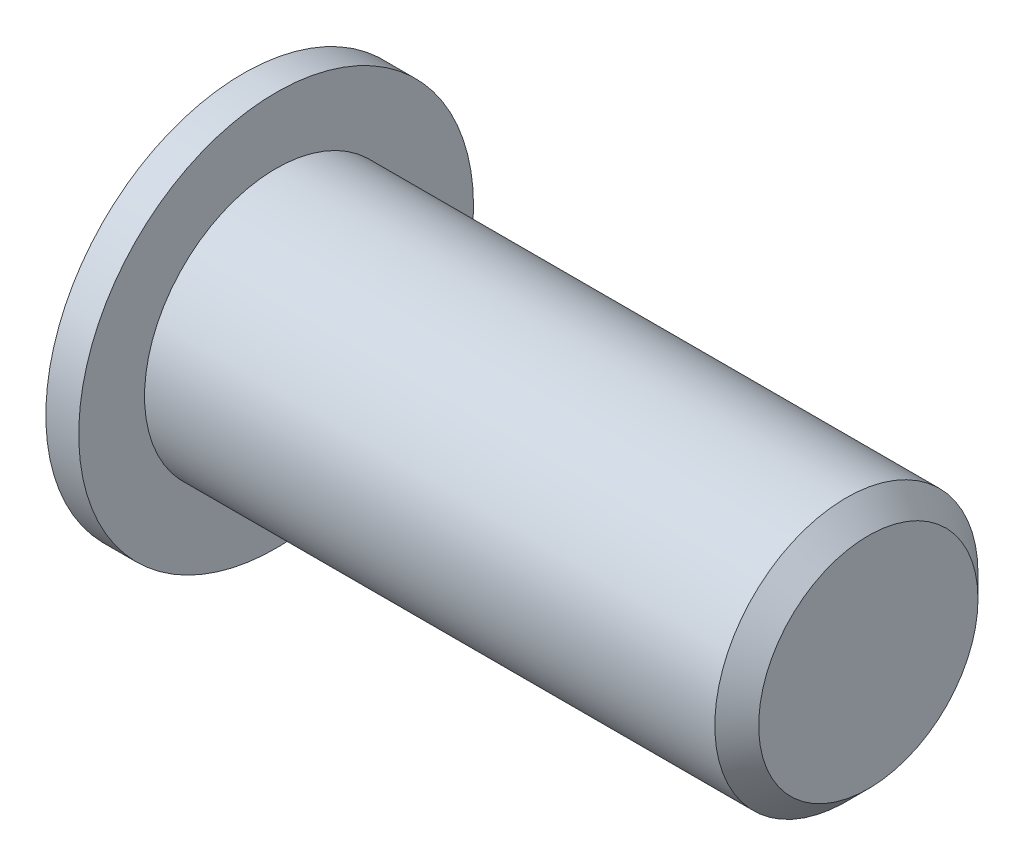
SolidWorks part; units mm, degrees
ref_plane "Front Plane" through (0, 0, 0) normal (0, 0, 1) x (1, 0, 0)
ref_plane "Top Plane" through (0, 0, 0) normal (0, 1, 0) x (1, 0, 0)
ref_plane "Right Plane" through (0, 0, 0) normal (1, 0, 0) x (0, 0, -1)
sketch "Sketch1" plane through (0, 0, 0) normal (0, 1, 0) x (1, 0, 0)
  line L0 (0, 0) -> (0.5, 0)
  line L1 (0.5, 0) -> (0.5, -1)
  line L2 (0.5, -1) -> (9.5, -1)
  line L3 (9.5, -1) -> (9.5, -3)
  line L4 (9.5, -3) -> (0, -3)
  line L5 (0, -3) -> (0, 0)
  dimension "D1" = 9
  dimension "D2" = 0.5
  dimension "D3" = 2
  dimension "D4" = 3
revolve "Revolve1" add sketch "Sketch1" angle 360 about L4
chamfer "Chamfer5" distance 0.3333 angle 45 1 edges at (9.5, 0, 1)
